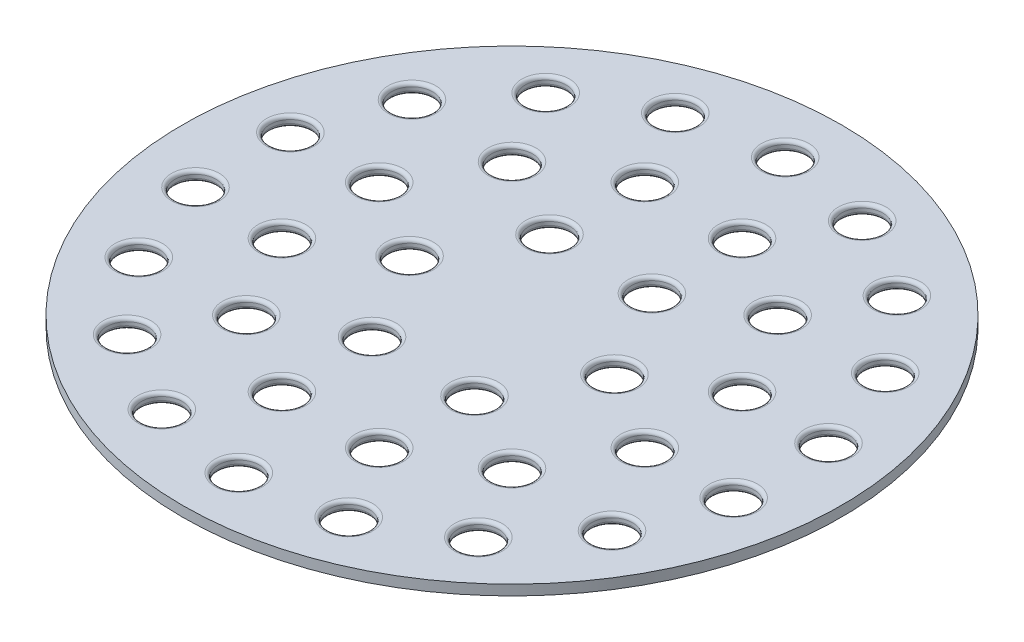
SolidWorks part; units mm, degrees
ref_plane "Front Plane" through (0, 0, 0) normal (0, 0, 1) x (1, 0, 0)
ref_plane "Top Plane" through (0, 0, 0) normal (0, 1, 0) x (1, 0, 0)
ref_plane "Right Plane" through (0, 0, 0) normal (1, 0, 0) x (0, 0, -1)
sketch "Sketch1" plane through (0, 0, 0) normal (0, 1, 0) x (1, 0, 0)
  circle A0 centre (0, 0) radius 96.5
  dimension "D1" = 193
extrude "Boss-Extrude1" add sketch "Sketch1" along normal blind 3
sketch "Sketch2" plane through (0, 3, 0) normal (0, 1, 0) x (1, 0, 0)
  line L0 (0, 0) -> (53.1259, 14.235) construction
  line L1 (0, 0) -> (78.7846, 13.8919) construction
  line L2 (0, 0) -> (67.4302, 0) construction
  circle A0 centre (30, 0) radius 6
  circle A1 centre (53.1259, 14.235) radius 6
  circle A2 centre (78.7846, 13.8919) radius 6
  circle A3 centre (15, -25.9808) radius 6
  circle A4 centre (-15, -25.9808) radius 6
  circle A5 centre (-30, 0) radius 6
  circle A6 centre (-15, 25.9808) radius 6
  circle A7 centre (15, 25.9808) radius 6
  circle A8 centre (53.1259, -14.235) radius 6
  circle A9 centre (38.8909, -38.8909) radius 6
  circle A10 centre (14.235, -53.1259) radius 6
  circle A11 centre (-14.235, -53.1259) radius 6
  circle A12 centre (-38.8909, -38.8909) radius 6
  circle A13 centre (-53.1259, -14.235) radius 6
  circle A14 centre (-53.1259, 14.235) radius 6
  circle A15 centre (-38.8909, 38.8909) radius 6
  circle A16 centre (-14.235, 53.1259) radius 6
  circle A17 centre (14.235, 53.1259) radius 6
  circle A18 centre (38.8909, 38.8909) radius 6
  circle A19 centre (78.7846, -13.8919) radius 6
  circle A20 centre (69.282, -40) radius 6
  circle A21 centre (51.423, -61.2836) radius 6
  circle A22 centre (27.3616, -75.1754) radius 6
  circle A23 centre (0, -80) radius 6
  circle A24 centre (-27.3616, -75.1754) radius 6
  circle A25 centre (-51.423, -61.2836) radius 6
  circle A26 centre (-69.282, -40) radius 6
  circle A27 centre (-78.7846, -13.8919) radius 6
  circle A28 centre (-78.7846, 13.8919) radius 6
  circle A29 centre (-69.282, 40) radius 6
  circle A30 centre (-51.423, 61.2836) radius 6
  circle A31 centre (-27.3616, 75.1754) radius 6
  circle A32 centre (0, 80) radius 6
  circle A33 centre (27.3616, 75.1754) radius 6
  circle A34 centre (51.423, 61.2836) radius 6
  circle A35 centre (69.282, 40) radius 6
  point P18 (0, 0)
  point P41 (0, 0)
  point P76 (0, 0)
  dimension "D2" = 12
  dimension "D3" = 12
  dimension "D4" = 12
  dimension "D1" = 6
  dimension "D7" = 55
  dimension "D8" = 80
  dimension "D9" = 15
  dimension "D10" = 10
  dimension "D5" = 12
  dimension "D6" = 18
extrude "Cut-Extrude3" cut sketch "Sketch2" against normal blind 10
fillet "Fillet1" radius 1 72 edges at (30, 0, 6) (69.282, 0, -34) (51.423, 0, -55.2836) (27.3616, 0, -69.1754) (-14.235, 0, -47.1259) (-38.8909, 0, -32.8909) (-53.1259, 0, -8.235) (-53.1259, 0, 20.235) (-38.8909, 0, 44.8909) (-14.235, 0, 59.1259) (14.235, 0, 59.1259) (38.8909, 0, 44.8909) (53.1259, 0, -8.235) (78.7846, 0, -7.8919) (15, 0, 31.9808) (-15, 0, 31.9808) (-30, 0, 6) (15, 0, -19.9808) (53.1259, 0, 20.235) (0, 0, -74) (-27.3616, 0, -69.1754) (-51.423, 0, -55.2836) (-69.282, 0, -34) (-78.7846, 0, -7.8919) (-78.7846, 0, 19.8919) (-69.282, 0, 46) (-51.423, 0, 67.2836) (-27.3616, 0, 81.1754) (0, 0, 86) (27.3616, 0, 81.1754) (51.423, 0, 67.2836) (69.282, 0, 46) (78.7846, 0, 19.8919) (38.8909, 0, -32.8909) (14.235, 0, -47.1259) (-15, 0, -19.9808) (30, 3, 6) (69.282, 3, -34) (51.423, 3, -55.2836) (27.3616, 3, -69.1754) (-14.235, 3, -47.1259) (-38.8909, 3, -32.8909) (-53.1259, 3, -8.235) (-53.1259, 3, 20.235) (-38.8909, 3, 44.8909) (-14.235, 3, 59.1259) (14.235, 3, 59.1259) (38.8909, 3, 44.8909) (53.1259, 3, -8.235) (78.7846, 3, -7.8919) (15, 3, 31.9808) (-15, 3, 31.9808) (-30, 3, 6) (-15, 3, -19.9808) (15, 3, -19.9808) (53.1259, 3, 20.235) (0, 3, -74) (-27.3616, 3, -69.1754) (-51.423, 3, -55.2836) (-69.282, 3, -34) (-78.7846, 3, -7.8919) (-78.7846, 3, 19.8919) (-69.282, 3, 46) (-51.423, 3, 67.2836) (-27.3616, 3, 81.1754) (27.3616, 3, 81.1754) (51.423, 3, 67.2836) (69.282, 3, 46) (78.7846, 3, 19.8919) (38.8909, 3, -32.8909) (14.235, 3, -47.1259) (0, 3, 86)
